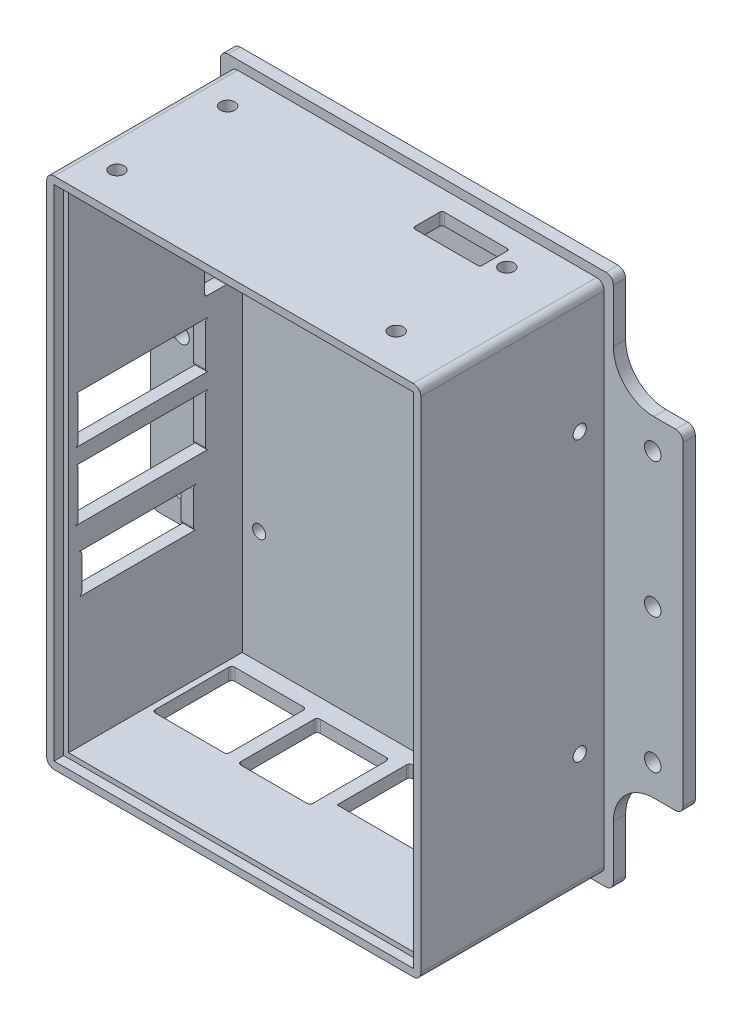
SolidWorks part; units mm, degrees
ref_plane "Front Plane" through (0, 0, 0) normal (0, 0, 1) x (1, 0, 0)
ref_plane "Top Plane" through (0, 0, 0) normal (0, 1, 0) x (1, 0, 0)
ref_plane "Right Plane" through (0, 0, 0) normal (1, 0, 0) x (0, 0, -1)
sketch "Sketch1" plane through (0, 0, 0) normal (0, 0, 1) x (1, 0, 0)
  line L0 (-40.8141, 42.7469) -> (-40.8141, 53.7324)
  line L1 (-39.2393, -55.3098) -> (39.2467, -55.3098)
  line L2 (-40.8141, -53.735) -> (-40.8141, -42.7495)
  line L3 (-39.2393, 55.3072) -> (39.2467, 55.3072)
  line L4 (40.8215, -53.735) -> (40.8215, -42.7495)
  line L9 (-49.2469, 34.3141) -> (-53.73, 34.3141)
  line L11 (-49.2469, -34.3167) -> (-53.73, -34.3167)
  line L12 (-55.3048, 32.7393) -> (-55.3048, -32.7419)
  line L13 (49.2543, -34.3167) -> (53.7374, -34.3167)
  line L15 (49.2543, 34.3141) -> (53.7374, 34.3141)
  line L16 (55.3122, -32.7419) -> (55.3122, 32.7393)
  line L17 (40.8215, 42.7469) -> (40.8215, 53.7324)
  circle A0 centre (49, -28) radius 1.7145
  arc A1 (-49.2469, 34.3141) -> (-40.8141, 42.7469) centre (-49.2469, 42.7469) ccw
  arc A2 (40.8215, 42.7469) -> (49.2543, 34.3141) centre (49.2543, 42.7469) ccw
  arc A3 (49.2543, -34.3167) -> (40.8215, -42.7495) centre (49.2543, -42.7495) ccw
  arc A4 (-40.8141, -42.7495) -> (-49.2469, -34.3167) centre (-49.2469, -42.7495) ccw
  arc A6 (-53.73, 34.3141) -> (-55.3048, 32.7393) centre (-53.73, 32.7393) ccw
  arc A7 (-55.3048, -32.7419) -> (-53.73, -34.3167) centre (-53.73, -32.7419) ccw
  arc A8 (-40.8141, -53.735) -> (-39.2393, -55.3098) centre (-39.2393, -53.735) ccw
  arc A9 (39.2467, -55.3098) -> (40.8215, -53.735) centre (39.2467, -53.735) ccw
  arc A10 (53.7374, -34.3167) -> (55.3122, -32.7419) centre (53.7374, -32.7419) ccw
  arc A11 (55.3122, 32.7393) -> (53.7374, 34.3141) centre (53.7374, 32.7393) ccw
  arc A12 (40.8215, 53.7324) -> (39.2467, 55.3072) centre (39.2467, 53.7324) ccw
  arc A13 (-40.8141, 53.7324) -> (-39.2393, 55.3072) centre (-39.2393, 53.7324) cw
  circle A15 centre (49, 0) radius 1.7145
  circle A17 centre (49, 28) radius 1.7145
  circle A19 centre (-49, -28) radius 1.7145
  circle A20 centre (-49, 0) radius 1.7145
  circle A21 centre (-49, 28) radius 1.7145
  point P19 (-40.8141, 34.3141)
  point P26 (-55.3048, 34.3141)
  point P29 (-55.3048, -34.3167)
  point P40 (40.8215, 55.3072)
  point P43 (-40.8141, 55.3072)
  dimension "D5" = 8.4328
  dimension "D6" = 1.5748
  dimension "D7" = 3.429
  dimension "D1" = 68.6308
  dimension "D2" = 81.6356
  dimension "D3" = 110.617
  dimension "D4" = 110.617
extrude "Base" add sketch "Sketch1" along normal blind 2.54
sketch "Sketch2" plane through (0, 0, 2.54) normal (0, 0, 1) x (1, 0, 0)
  line L0 (-40.8141, 53.7324) -> (-40.8141, 42.7469) construction
  line L1 (-37.2399, 53.4022) -> (37.3417, 53.4022)
  line L2 (-38.8147, 51.8274) -> (-38.8147, 34.3141)
  line L3 (-37.2399, -53.4048) -> (37.3417, -53.4048)
  line L4 (38.9165, 51.8274) -> (38.9165, -51.83)
  line L5 (39.2467, 55.3072) -> (-39.2393, 55.3072) construction
  line L6 (40.8215, 42.7469) -> (40.8215, 53.7324) construction
  line L7 (-39.2393, -55.3098) -> (39.2467, -55.3098) construction
  line L8 (-36.2747, 50.8622) -> (-36.2747, -50.8648)
  line L9 (-36.2747, -50.8648) -> (36.3765, -50.8648)
  line L10 (36.3765, 50.8622) -> (36.3765, -50.8648)
  line L11 (-36.2747, 50.8622) -> (36.3765, 50.8622)
  line L12 (-53.73, -34.3167) -> (-49.2469, -34.3167) construction
  line L13 (-38.8147, 34.3141) -> (-44.2985, 34.3141)
  line L15 (-38.8147, 31.1391) -> (-44.2985, 31.1391)
  line L16 (-44.2985, 34.3141) -> (-44.2985, 31.1391)
  line L17 (-38.8147, -34.3167) -> (-44.2985, -34.3167)
  line L19 (-38.8147, -31.1417) -> (-44.2985, -31.1417)
  line L20 (-44.2985, -34.3167) -> (-44.2985, -31.1417)
  line L21 (-49.2469, 34.3141) -> (-53.73, 34.3141) construction
  line L22 (-38.8147, 31.1391) -> (-38.8147, -31.1417)
  line L23 (-38.8147, -34.3167) -> (-38.8147, -51.83)
  line L24 (-38.8147, 51.8274) -> (-38.8147, -51.83) construction
  arc A0 (-37.2399, 53.4022) -> (-38.8147, 51.8274) centre (-37.2399, 51.8274) ccw
  arc A1 (38.9165, 51.8274) -> (37.3417, 53.4022) centre (37.3417, 51.8274) ccw
  arc A2 (38.9165, -51.83) -> (37.3417, -53.4048) centre (37.3417, -51.83) cw
  arc A3 (-38.8147, -51.83) -> (-37.2399, -53.4048) centre (-37.2399, -51.83) ccw
  arc A4 (-36.2747, -50.8648) -> (-36.2747, -50.8648) centre (-36.2747, -50.8648) ccw
  arc A5 (36.3765, -50.8648) -> (36.3765, -50.8648) centre (36.3765, -50.8648) cw
  arc A6 (36.3765, 50.8622) -> (36.3765, 50.8622) centre (36.3765, 50.8622) ccw
  arc A7 (-36.2747, 50.8622) -> (-36.2747, 50.8622) centre (-36.2747, 50.8622) ccw
  dimension "D5" = 1.5748
  dimension "D1" = 1.9994
  dimension "D2" = 1.905
  dimension "D3" = 1.905
  dimension "D4" = 1.905
  dimension "D7" = 3.175
  dimension "D8" = 3.175
  dimension "D6" = 2.54
extrude "Wall" add sketch "Sketch2" along normal blind 38.1
sketch "Sketch4" plane through (0, -50.8648, 0) normal (0, 1, 0) x (1, 0, 0)
  line L0 (-36.2747, -40.64) -> (-36.2747, -2.54) construction
  line L5 (-20.1597, -5.9888) -> (-34.3897, -5.9888)
  line L6 (-19.5247, -6.6238) -> (-19.5247, -21.8538)
  line L7 (-20.1597, -22.4888) -> (-34.3897, -22.4888)
  line L8 (-35.0247, -6.6238) -> (-35.0247, -21.8538)
  line L10 (-16.1397, -6.4734) -> (-2.4097, -6.4734)
  line L11 (-16.7747, -7.1084) -> (-16.7747, -22.3384)
  line L12 (-16.1397, -22.9734) -> (-2.4097, -22.9734)
  line L13 (-1.7747, -7.1084) -> (-1.7747, -22.3384)
  line L15 (1.0092, -20.1273) -> (17.9414, -20.1273)
  line L16 (1.0092, -20.1273) -> (1.0092, -5.6905)
  line L17 (1.6442, -5.0555) -> (17.3064, -5.0555)
  line L18 (17.9414, -20.1273) -> (17.9414, -5.6905)
  arc A0 (17.3064, -5.0555) -> (17.9414, -5.6905) centre (17.3064, -5.6905) cw
  arc A1 (1.0092, -5.6905) -> (1.6442, -5.0555) centre (1.6442, -5.6905) cw
  arc A2 (-2.4097, -6.4734) -> (-1.7747, -7.1084) centre (-2.4097, -7.1084) cw
  arc A3 (-2.4097, -22.9734) -> (-1.7747, -22.3384) centre (-2.4097, -22.3384) ccw
  arc A4 (-16.7747, -22.3384) -> (-16.1397, -22.9734) centre (-16.1397, -22.3384) ccw
  arc A5 (-16.7747, -7.1084) -> (-16.1397, -6.4734) centre (-16.1397, -7.1084) cw
  arc A6 (-20.1597, -5.9888) -> (-19.5247, -6.6238) centre (-20.1597, -6.6238) cw
  arc A7 (-20.1597, -22.4888) -> (-19.5247, -21.8538) centre (-20.1597, -21.8538) ccw
  arc A8 (-35.0247, -21.8538) -> (-34.3897, -22.4888) centre (-34.3897, -21.8538) ccw
  arc A9 (-35.0247, -6.6238) -> (-34.3897, -5.9888) centre (-34.3897, -6.6238) cw
  point P4 (-27.2747, -22.4888)
  point P11 (-9.2747, -22.9734)
  point P18 (9.4753, -5.0555)
  point P25 (-1.7747, -22.9734)
  point P28 (-16.7747, -22.9734)
  point P35 (-19.5247, -22.4888)
  point P38 (-35.0247, -22.4888)
  point P41 (-35.0247, -5.9888)
  dimension "D7" = 0.635
  dimension "D1" = 9
  dimension "D2" = 15.5
  dimension "D3" = 16.5
  dimension "D4" = 15
  dimension "D5" = 27
  dimension "D6" = 45.75
extrude "USB + Eth" cut sketch "Sketch4" against normal up to surface (2.54 mm away) up to face at (0.0509, -53.4048, 21.59)
sketch "Sketch5" plane through (-36.2747, 0, 0) normal (1, 0, 0) x (0, 0, -1)
  line L0 (-35.8886, 19.5703) -> (-35.8886, 18.8809) construction
  line L1 (-9.6328, 17.7214) -> (-6.0768, 17.7214) construction
  line L2 (-9.6328, 17.7214) -> (-9.6328, 28.149) construction
  line L3 (-9.6328, 28.149) -> (-6.0768, 28.149) construction
  line L4 (-6.0768, 17.7214) -> (-6.0768, 28.149) construction
  line L5 (-10.9178, 4.0093) -> (-35.8886, 4.0093) construction
  line L6 (-10.9178, 4.0093) -> (-10.9178, 12.261) construction
  line L7 (-10.9178, 12.261) -> (-35.8886, 12.261) construction
  line L8 (-35.8886, 4.0093) -> (-35.8886, 12.261) construction
  line L9 (-35.8886, -27.3648) -> (-40.64, -27.3648) construction
  line L10 (-10.9178, -10.0317) -> (-35.8886, -10.0317) construction
  line L11 (-10.9178, -10.0317) -> (-10.9178, -0.6979) construction
  line L12 (-10.9178, -0.6979) -> (-35.8886, -0.6979) construction
  line L13 (-35.8886, -10.0317) -> (-35.8886, -0.6979) construction
  line L14 (-12.0908, -23.9547) -> (-36.5236, -23.9547)
  line L15 (-12.7258, -23.3197) -> (-12.7258, -16.41)
  line L16 (-12.0908, -15.775) -> (-36.5236, -15.775)
  line L17 (-35.8886, -23.3197) -> (-35.8886, -16.41)
  line L18 (-40.64, 50.8622) -> (-40.64, -50.8648) construction
  line L19 (-40.64, -50.8648) -> (-2.54, -50.8648) construction
  line L20 (-27.94, 30.6352) -> (-2.54, 30.6352) construction
  line L21 (-2.54, 50.8622) -> (-2.54, -50.8648) construction
  line L22 (-10.3828, 17.6064) -> (-10.3828, 28.264)
  line L23 (-9.7478, 28.899) -> (-5.9618, 28.899)
  line L24 (-5.3268, 17.6064) -> (-5.3268, 28.264)
  line L25 (-9.7478, 16.9714) -> (-5.9618, 16.9714)
  line L26 (-10.1678, 3.8943) -> (-10.1678, 12.376)
  line L27 (-9.5328, 13.011) -> (-37.2736, 13.011)
  line L28 (-36.6386, 3.8943) -> (-36.6386, 12.376)
  line L29 (-9.5328, 3.2593) -> (-37.2736, 3.2593)
  line L30 (-10.1678, -10.1467) -> (-10.1678, -0.5829)
  line L31 (-9.5328, 0.0521) -> (-37.2736, 0.0521)
  line L32 (-36.6386, -10.1467) -> (-36.6386, -0.5829)
  line L33 (-9.5328, -10.7817) -> (-37.2736, -10.7817)
  line L34 (-36.6386, -10.7817) -> (-36.6386, 0.0521) construction
  line L35 (-10.1678, -10.7817) -> (-36.6386, -10.7817) construction
  line L36 (-10.1678, -10.7817) -> (-10.1678, 0.0521) construction
  line L37 (-10.1678, 0.0521) -> (-36.6386, 0.0521) construction
  line L38 (-10.1678, 3.2593) -> (-10.1678, 13.011) construction
  line L39 (-10.1678, 3.2593) -> (-36.6386, 3.2593) construction
  line L40 (-36.6386, 3.2593) -> (-36.6386, 13.011) construction
  line L41 (-10.1678, 13.011) -> (-36.6386, 13.011) construction
  line L42 (-10.3828, 16.9714) -> (-10.3828, 28.899) construction
  line L43 (-10.3828, 28.899) -> (-5.3268, 28.899) construction
  line L44 (-5.3268, 16.9714) -> (-5.3268, 28.899) construction
  line L45 (-10.3828, 16.9714) -> (-5.3268, 16.9714) construction
  arc A0 (-36.6386, -10.1467) -> (-37.2736, -10.7817) centre (-37.2736, -10.1467) cw
  arc A1 (-10.1678, -10.1467) -> (-9.5328, -10.7817) centre (-9.5328, -10.1467) ccw
  arc A2 (-10.1678, -0.5829) -> (-9.5328, 0.0521) centre (-9.5328, -0.5829) cw
  arc A3 (-37.2736, 0.0521) -> (-36.6386, -0.5829) centre (-37.2736, -0.5829) cw
  arc A4 (-10.1678, 3.8943) -> (-9.5328, 3.2593) centre (-9.5328, 3.8943) ccw
  arc A5 (-36.6386, 3.8943) -> (-37.2736, 3.2593) centre (-37.2736, 3.8943) cw
  arc A6 (-37.2736, 13.011) -> (-36.6386, 12.376) centre (-37.2736, 12.376) cw
  arc A7 (-9.5328, 13.011) -> (-10.1678, 12.376) centre (-9.5328, 12.376) ccw
  arc A8 (-10.3828, 28.264) -> (-9.7478, 28.899) centre (-9.7478, 28.264) cw
  arc A9 (-5.3268, 28.264) -> (-5.9618, 28.899) centre (-5.9618, 28.264) ccw
  arc A10 (-5.9618, 16.9714) -> (-5.3268, 17.6064) centre (-5.9618, 17.6064) ccw
  arc A11 (-10.3828, 17.6064) -> (-9.7478, 16.9714) centre (-9.7478, 17.6064) ccw
  arc A13 (-36.5236, -15.775) -> (-35.8886, -16.41) centre (-36.5236, -16.41) cw
  arc A14 (-35.8886, -23.3197) -> (-36.5236, -23.9547) centre (-36.5236, -23.3197) cw
  arc A15 (-12.7258, -16.41) -> (-12.0908, -15.775) centre (-12.0908, -16.41) cw
  arc A16 (-12.7258, -23.3197) -> (-12.0908, -23.9547) centre (-12.0908, -23.3197) ccw
  point P28 (-9.6328, 22.9352)
  point P29 (-10.9178, 8.1352)
  point P30 (-12.7258, -19.8648)
  point P32 (-10.9178, -5.3648)
  point P83 (-35.8886, -15.775)
  dimension "D1" = 0.75
  dimension "D8" = 0.635
  dimension "D9" = 0.635
  dimension "D2" = 23.5
  dimension "D3" = 58
  dimension "D4" = 7.7
  dimension "D5" = 14.8
  dimension "D6" = 13.5
  dimension "D7" = 14.5
extrude "USBC + Audio + HDMI" cut sketch "Sketch5" along normal up to surface (2.54 mm away) from surface
sketch "Sketch6" plane through (0, 50.8622, 0) normal (0, -1, 0) x (-1, 0, 0)
  line L0 (36.2747, -40.64) -> (36.2747, -2.54) construction
  line L1 (-36.3765, -40.64) -> (36.2747, -40.64) construction
  line L2 (-22.7803, -12.72) -> (-9.7803, -12.72)
  line L3 (-22.7803, -12.22) -> (-9.7803, -12.22) construction
  line L4 (-22.7803, -12.22) -> (-22.7803, -7.1) construction
  line L5 (-22.7803, -7.1) -> (-9.7803, -7.1) construction
  line L6 (-9.7803, -12.22) -> (-9.7803, -7.1) construction
  line L7 (-9.2803, -12.22) -> (-9.2803, -7.1)
  line L8 (-22.7803, -6.6) -> (-9.7803, -6.6)
  line L9 (-23.2803, -12.22) -> (-23.2803, -7.1)
  line L10 (-23.2803, -12.72) -> (-9.2803, -12.72) construction
  line L11 (-9.2803, -12.72) -> (-9.2803, -6.6) construction
  line L12 (-23.2803, -6.6) -> (-9.2803, -6.6) construction
  line L13 (-23.2803, -12.72) -> (-23.2803, -6.6) construction
  circle A0 centre (31.8297, -33.02) radius 1.5
  circle A2 centre (31.8297, -10.02) radius 1.5
  circle A4 centre (-26.1703, -33.02) radius 1.5
  circle A6 centre (-26.1703, -10.02) radius 1.5
  arc A7 (-9.7803, -12.72) -> (-9.2803, -12.22) centre (-9.7803, -12.22) ccw
  arc A8 (-9.7803, -6.6) -> (-9.2803, -7.1) centre (-9.7803, -7.1) cw
  arc A9 (-23.2803, -7.1) -> (-22.7803, -6.6) centre (-22.7803, -7.1) cw
  arc A10 (-22.7803, -12.72) -> (-23.2803, -12.22) centre (-22.7803, -12.22) cw
  point P4 (-16.2803, -12.22)
  point P14 (-22.7803, -9.66)
  dimension "D1" = 3
  dimension "D11" = 0.5
  dimension "D3" = 4.445
  dimension "D4" = 7.62
  dimension "D5" = 23
  dimension "D6" = 58
  dimension "D2" = 0.5
  dimension "D7" = 23.36
  dimension "D8" = 5.12
  dimension "D9" = 13
  dimension "D10" = 9.89
extrude "BerryGPS Mount" cut sketch "Sketch6" against normal up to surface (2.54 mm away) up to face at (0.0509, 53.4022, 21.59)
sketch "Sketch7" plane through (0, 0, 40.64) normal (0, 0, 1) x (1, 0, 0)
  line L14 (37.3765, -51.8648) -> (37.3765, 51.8622)
  line L15 (-37.2747, -51.8648) -> (37.3765, -51.8648)
  line L16 (-37.2747, 51.8622) -> (-37.2747, -51.8648)
  line L17 (37.3765, 51.8622) -> (-37.2747, 51.8622)
  line L18 (37.3765, -51.8648) -> (37.3765, 51.8622)
  line L19 (-37.2747, -51.8648) -> (37.3765, -51.8648)
  line L20 (-37.2747, 51.8622) -> (-37.2747, -51.8648)
  line L21 (37.3765, 51.8622) -> (-37.2747, 51.8622)
  dimension "D1" = 1
extrude "Lid ridge" cut sketch "Sketch7" against normal blind 2
sketch "Sketch9" plane through (0, -34.3167, 0) normal (0, -1, 0) x (1, 0, 0)
  line L0 (-38.8147, 40.64) -> (-44.2985, 2.54)
  line L1 (-38.8147, 40.64) -> (-38.8147, 2.54) construction
  line L2 (-40.8141, 2.54) -> (-49.2469, 2.54) construction
  line L3 (-44.2985, 40.64) -> (-44.2985, 2.54) construction
  line L4 (-38.8147, 40.64) -> (-44.2985, 40.64)
  line L5 (-44.2985, 40.64) -> (-38.8147, 40.64) construction
  line L6 (-44.2985, 40.64) -> (-44.2985, 2.54)
extrude "Cut-Extrude6" cut sketch "Sketch9" against normal up to surface (68.6308 mm away) up to face at (-41.5566, 34.3141, 21.59)
sketch "Sketch10" plane through (0, 0, 2.54) normal (0, 0, 1) x (1, 0, 0)
  line L0 (36.3765, -50.8648) -> (36.3765, 50.8622) construction
  line L1 (32.1897, 40.7487) -> (29.0397, 40.7487)
  line L2 (32.1897, 40.7487) -> (32.1897, 28.2487)
  line L3 (32.1897, -40.7513) -> (22.8897, -40.7513)
  line L4 (22.8897, 40.7487) -> (22.8897, -40.7513)
  line L5 (26.0397, 40.7487) -> (22.8897, 40.7487)
  line L6 (32.1897, 25.2487) -> (32.1897, -25.2513)
  line L7 (32.1897, -28.2513) -> (32.1897, -40.7513)
  line L8 (32.1897, -0.0013) -> (36.3765, -0.0013) construction
  line L9 (22.8897, -0.0013) -> (18.7029, -0.0013) construction
  arc A0 (29.0397, 40.7487) -> (26.0397, 40.7487) centre (27.5397, 40.7487) ccw
  arc A1 (32.1897, 28.2487) -> (32.1897, 25.2487) centre (32.1897, 26.7487) cw
  arc A2 (32.1897, -25.2513) -> (32.1897, -28.2513) centre (32.1897, -26.7513) cw
  dimension "D3" = 1.5
  dimension "D4" = 1.5
  dimension "D6" = 1.5
  dimension "D1" = 81.5
  dimension "D2" = 9.3
  dimension "D5" = 14
  dimension "D7" = 14
extrude "Breadboard slice" cut sketch "Sketch10" against normal blind 2
sketch "Sketch11" plane through (0, 0, 2.54) normal (0, 0, 1) x (1, 0, 0)
  circle A0 centre (-32.7747, 30.6352) radius 1.35
  circle A1 centre (16.2253, 30.6352) radius 1.35
  circle A2 centre (16.2253, -27.3648) radius 1.35
  circle A3 centre (-32.7747, -27.3648) radius 1.35
  dimension "D1" = 2.7
extrude "Pi Mounting" cut sketch "Sketch11" against normal up to surface (2.54 mm away) up to face at (0.0037, -0.0013, 0)
sketch "Sketch12" plane through (38.9165, 0, 0) normal (1, 0, 0) x (0, 0, -1)
  line L2 (-7.62, 28.9987) -> (-7.62, -29.0013) construction
  line L3 (-2.54, -51.83) -> (-2.54, 51.8274) construction
  circle A0 centre (-7.62, 28.9987) radius 1.375
  circle A1 centre (-7.62, -29.0013) radius 1.375
  point P6 (-2.54, -0.0013)
  point P7 (-7.62, -0.0013)
  dimension "D1" = 2.75
  dimension "D2" = 58
  dimension "D3" = 5.08
extrude "Cut-Extrude7" cut sketch "Sketch12" against normal up to surface (2.54 mm away) up to face at (36.3765, -0.0013, 20.59)
